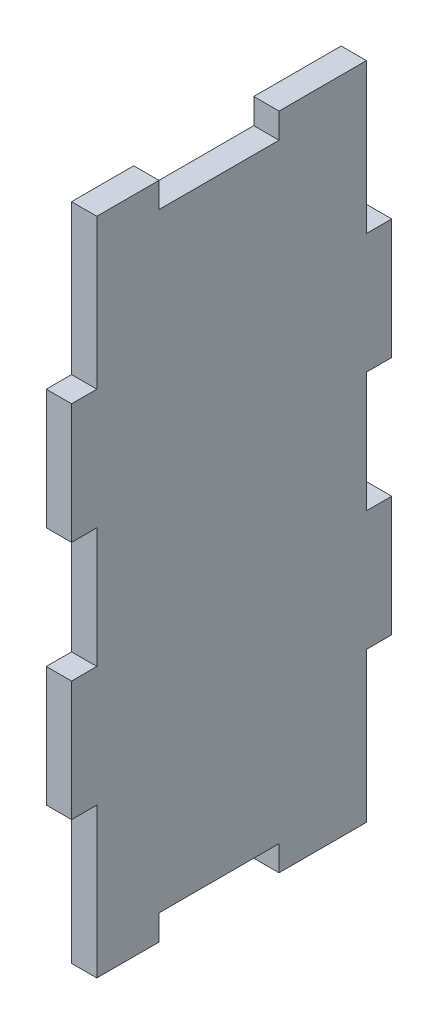
SolidWorks part; units mm, degrees
ref_plane "Front Plane" through (0, 0, 0) normal (0, 0, 1) x (1, 0, 0)
ref_plane "Top Plane" through (0, 0, 0) normal (0, 1, 0) x (1, 0, 0)
ref_plane "Right Plane" through (0, 0, 0) normal (1, 0, 0) x (0, 0, -1)
sketch "Sketch1" plane through (0, 0, 0) normal (1, 0, 0) x (0, 0, -1)
  line L66 (-16.7197, 37.3294) -> (-16.7197, 19.5544)
  line L67 (-16.7197, 19.5544) -> (-19.7197, 19.5544)
  line L68 (-19.7197, 19.5544) -> (-19.7197, 5.3044)
  line L69 (-19.7197, 5.3044) -> (-16.7197, 5.3044)
  line L70 (-16.7197, 5.3044) -> (-16.7197, -8.9456)
  line L71 (-16.7197, -8.9456) -> (-19.7197, -8.9456)
  line L72 (-19.7197, -8.9456) -> (-19.7197, -23.1956)
  line L73 (-19.7197, -23.1956) -> (-16.7197, -23.1956)
  line L74 (-16.7197, -23.1956) -> (-16.7197, -37.4456)
  line L75 (-16.7197, -37.4456) -> (-16.7197, -40.9706)
  line L76 (-16.7197, -40.9706) -> (-9.3447, -40.9706)
  line L77 (-9.3447, -40.9706) -> (-9.3447, -37.9706)
  line L78 (-9.3447, -37.9706) -> (4.9053, -37.9706)
  line L79 (4.9053, -37.9706) -> (4.9053, -40.9706)
  line L80 (4.9053, -40.9706) -> (15.2803, -40.9706)
  line L81 (15.2803, -40.9706) -> (15.2803, -23.1956)
  line L82 (15.2803, -23.1956) -> (18.2803, -23.1956)
  line L83 (18.2803, -23.1956) -> (18.2803, -8.9456)
  line L84 (18.2803, -8.9456) -> (15.2803, -8.9456)
  line L85 (15.2803, -8.9456) -> (15.2803, 5.3044)
  line L86 (15.2803, 5.3044) -> (18.2803, 5.3044)
  line L87 (18.2803, 5.3044) -> (18.2803, 19.5544)
  line L88 (18.2803, 19.5544) -> (15.2803, 19.5544)
  line L89 (15.2803, 19.5544) -> (15.2803, 33.8044)
  line L90 (15.2803, 33.8044) -> (15.2803, 37.3294)
  line L91 (15.2803, 37.3294) -> (4.9053, 37.3294)
  line L92 (4.9053, 37.3294) -> (4.9053, 34.3294)
  line L93 (4.9053, 34.3294) -> (-9.3447, 34.3294)
  line L94 (-9.3447, 34.3294) -> (-9.3447, 37.3294)
  line L95 (-9.3447, 37.3294) -> (-16.7197, 37.3294)
  dimension "D1" = 7.375
extrude "Boss-Extrude1" add sketch "Sketch1" along normal blind 3
